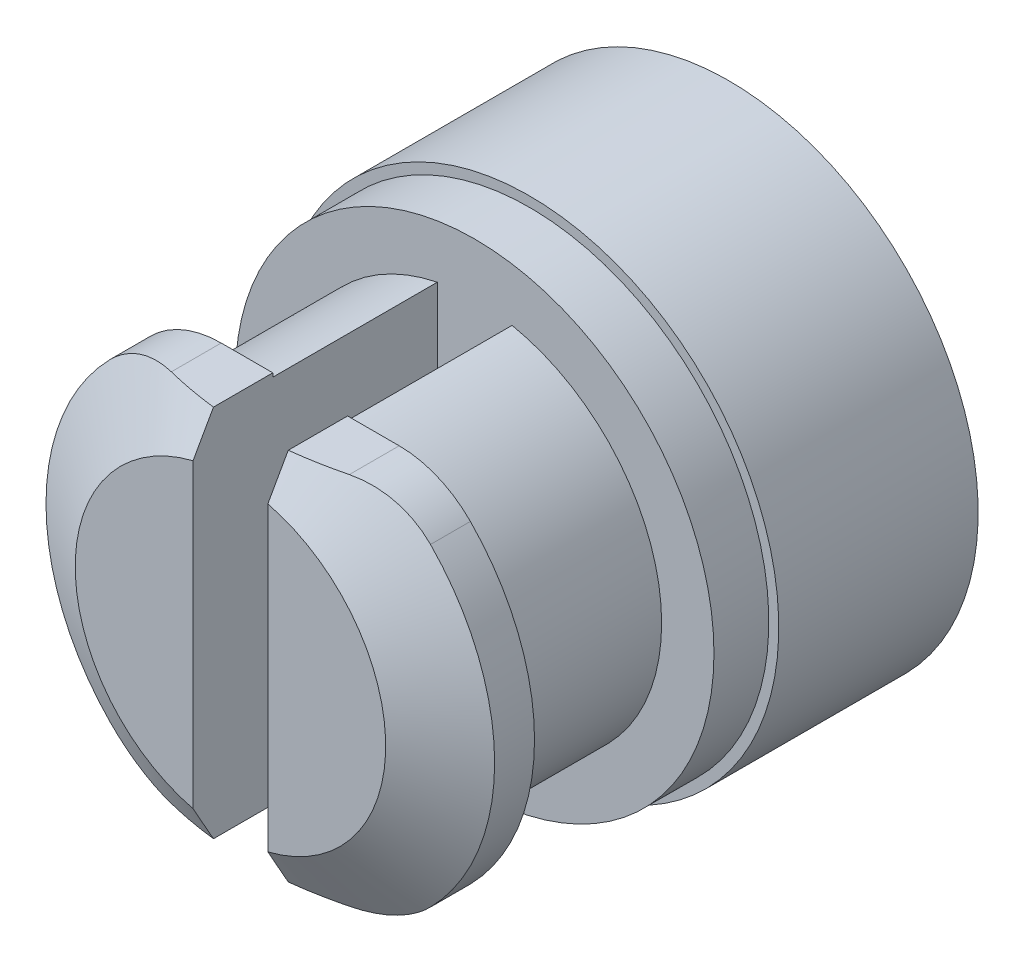
SolidWorks part; units mm, degrees
ref_plane "Front Plane" through (0, 0, 0) normal (0, 0, 1) x (1, 0, 0)
ref_plane "Top Plane" through (0, 0, 0) normal (0, 1, 0) x (1, 0, 0)
ref_plane "Right Plane" through (0, 0, 0) normal (1, 0, 0) x (0, 0, -1)
sketch "Sketch1" plane through (0, 0, 0) normal (0, 0, 1) x (1, 0, 0)
  circle A0 centre (0, 0) radius 2.4
  dimension "D1" = 4.8
extrude "Boss-Extrude1" add sketch "Sketch1" along normal blind 0.55
sketch "Sketch2" plane through (0, 0, 0.55) normal (0, 0, 1) x (1, 0, 0)
  circle A0 centre (0, 0) radius 1.875
  dimension "D1" = 3.75
extrude "Boss-Extrude2" add sketch "Sketch2" along normal blind 1.65
sketch "Sketch3" plane through (0, 0, 0) normal (0, 0, -1) x (-1, 0, 0)
  circle A0 centre (0, 0) radius 2.5
  dimension "D1" = 5
extrude "Boss-Extrude3" add sketch "Sketch3" along normal blind 2
sketch "Sketch4" plane through (0, 0, 2.2) normal (0, 0, 1) x (1, 0, 0)
  circle A0 centre (0, 0) radius 2.25
  dimension "D1" = 4.5
extrude "Boss-Extrude4" add sketch "Sketch4" along normal blind 0.8
sketch "Sketch5" plane through (0, 0, 3) normal (0, 0, 1) x (1, 0, 0)
  line L1 (-0.375, -3.0369) -> (0.375, -3.0369)
  line L2 (-0.375, -3.0369) -> (-0.375, 3.0369)
  line L3 (-0.375, 3.0369) -> (0.375, 3.0369)
  line L4 (0.375, -3.0369) -> (0.375, 3.0369)
  line L5 (-0.375, -3.0369) -> (0.375, 3.0369) construction
  line L6 (-0.375, 3.0369) -> (0.375, -3.0369) construction
  point P0 (0, 0)
  dimension "D1" = 0.75
extrude "Cut-Extrude1" cut sketch "Sketch5" against normal up to surface (2.45 mm away) up to face at (1.875, 0, 0.55)
chamfer "Chamfer1" distance 0.4 angle 60 2 edges at (-2.25, 0, 3) (2.25, 0, 3)
sketch "Sketch6" plane through (0, 0, 3) normal (0, 0, 1) x (1, 0, 0)
  line L1 (-3.2793, -1.875) -> (3.2793, -1.875)
  line L2 (-3.2793, -1.875) -> (-3.2793, 1.875)
  line L3 (-3.2793, 1.875) -> (3.2793, 1.875)
  line L4 (3.2793, -1.875) -> (3.2793, 1.875)
  line L5 (-3.2793, -1.875) -> (3.2793, 1.875) construction
  line L6 (-3.2793, 1.875) -> (3.2793, -1.875) construction
  line L7 (-3.4518, 2.624) -> (3.5474, 2.624)
  line L8 (-3.4518, 2.624) -> (-3.4518, -2.711)
  line L9 (-3.4518, -2.711) -> (3.5474, -2.711)
  line L10 (3.5474, 2.624) -> (3.5474, -2.711)
  point P0 (0, 0)
  dimension "D1" = 3.75
extrude "Cut-Extrude3" cut sketch "Sketch6" against normal blind 2
fillet "Fillet2" radius 1 4 edges at (-1.2437, 1.875, 2.4) (1.2437, 1.875, 2.4) (-1.2437, -1.875, 2.4) (1.2437, -1.875, 2.4)
sketch "Sketch7" plane through (0, 0, -2) normal (0, 0, -1) x (-1, 0, 0)
  circle A0 centre (0, 0) radius 1
  dimension "D1" = 2
extrude "Cut-Extrude4" cut sketch "Sketch7" against normal blind 2
sketch "Sketch8" plane through (0, 0, 0) normal (0, 1, 0) x (1, 0, 0)
  line L2 (-0.8927, -2.2) -> (-1.6068, -2.2) construction
  line L5 (-0.375, -2.2) -> (-0.375, -0.55) construction
  line L7 (-0.625, -1.2) -> (0, -1.2)
  line L8 (0, -1.2) -> (0, -2.2)
  line L9 (0, -2.2) -> (-0.625, -2.2)
  circle A0 centre (-0.625, -1.7) radius 0.5
  dimension "D1" = 1
  dimension "D2" = 0.5
  dimension "D3" = 0.25
